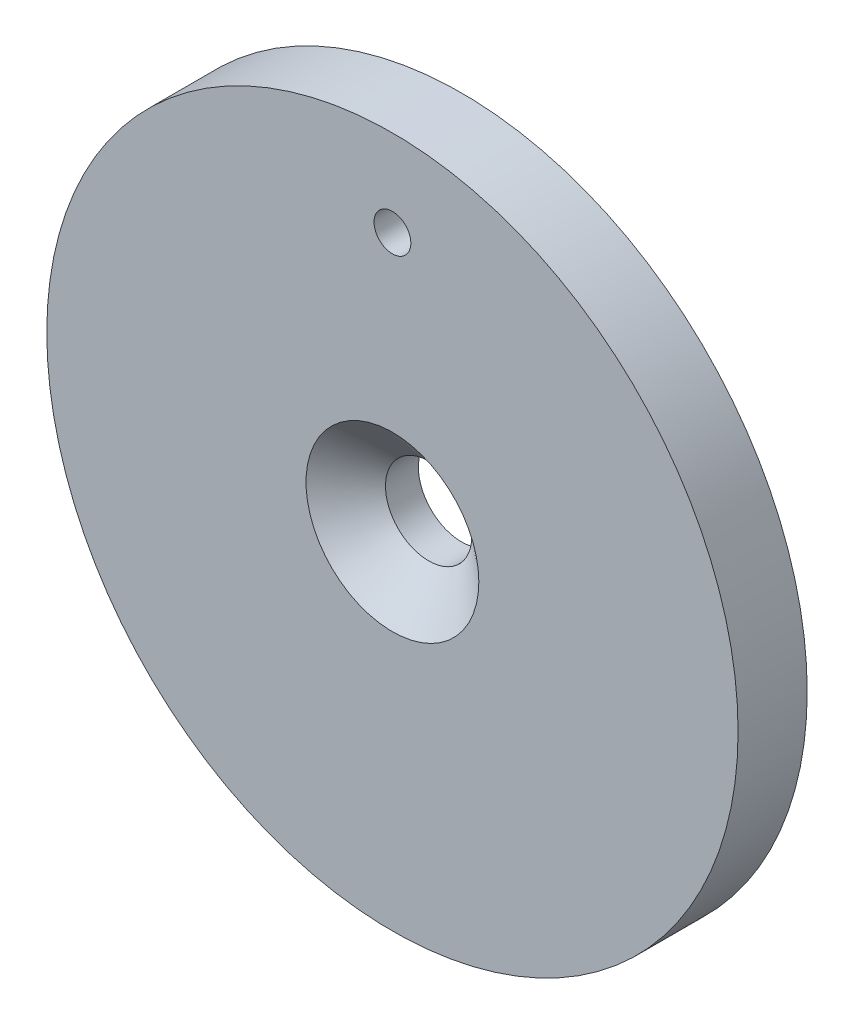
SolidWorks part; units mm, degrees
ref_plane "Front Plane" through (0, 0, 0) normal (0, 0, 1) x (1, 0, 0)
ref_plane "Top Plane" through (0, 0, 0) normal (0, 1, 0) x (1, 0, 0)
ref_plane "Right Plane" through (0, 0, 0) normal (1, 0, 0) x (0, 0, -1)
sketch "Sketch1" plane through (0, 0, 0) normal (0, 0, 1) x (1, 0, 0)
  circle A0 centre (0, 0) radius 25.4
  dimension "D1" = 50.8
extrude "Disc Base" add sketch "Sketch1" along normal blind 5.08
sketch "Sketch2" plane through (0, 0, 5.08) normal (0, 0, 1) x (1, 0, 0)
  circle A0 centre (0, 0) radius 3.175
  dimension "D1" = 6.35
sketch "Sketch3" plane through (0, 0, 5.08) normal (0, 0, 1) x (1, 0, 0)
  circle A0 centre (0, 19.05) radius 1.3589
  dimension "D1" = 2.7178
  dimension "D2" = 19.05
hole_wizard "CSK for 1/4 Flat Head Machine Screw (100)1" positions "3DSketch7" profile "Sketch10" countersink size "1/4" standard "ANSI Inch"
sketch3d "3DSketch7"
  point P0 (0, 0, 5.08)
sketch "Sketch10" plane through (0, 0, 5.08) normal (1, 0, 0) x (0, -1, 0)
  line L0 (0, 0) -> (0, 2.54)
  line L1 (0, 2.54) -> (3.175, 0.6323)
  line L2 (3.175, 0.6323) -> (3.175, 2.6641)
  line L3 (3.175, 2.6641) -> (6.35, 0)
  line L5 (6.35, 0) -> (0, 0)
  line L6 (-3.175, 2.6641) -> (-6.35, 0) construction
  line L10 (0, 2.54) -> (-3.175, 0.6323) construction
  line L11 (0, -6.35) -> (0, 107.95) construction
  dimension "Hole Dia." = 6.35
  dimension "Hole Depth" = 2.54
  dimension "Near C'Sink Dia." = 12.7
  dimension "Near C'Sink Angle" = 100
  dimension "Drill Angle" = 118
extrude "Cut-Extrude2" cut sketch "Sketch2" against normal through all contours A0
hole_wizard "#6-32 Tapped Hole1" positions "3DSketch8" profile "Sketch11" tap size "#6-32" standard "ANSI Inch" end condition through all
sketch3d "3DSketch8"
  point P0 (0, 19.05, 5.08)
sketch "Sketch11" plane through (0, 19.05, 5.08) normal (1, 0, 0) x (0, -1, 0)
  line L0 (0, 0) -> (0, 5.08)
  line L1 (0, 5.08) -> (1.3525, 5.08)
  line L2 (1.3525, 5.08) -> (1.3525, 0)
  line L5 (1.3525, 0) -> (0, 0)
  line L11 (0, -6.35) -> (0, 107.95) construction
  dimension "Thru Tap Drill Dia." = 2.7051
  dimension "Thru Tap Drill Depth" = 5.08
cosmetic thread "Hole Thread1"
